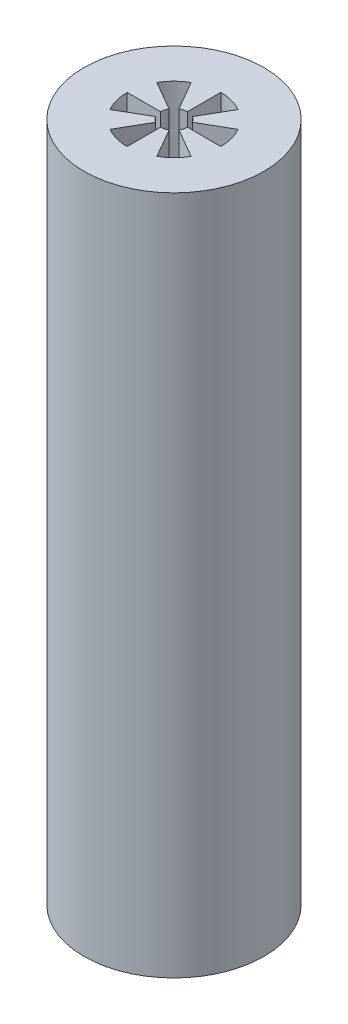
SolidWorks part; units mm, degrees
material "PE High Density"
ref_plane "Front Plane" through (0, 0, 0) normal (0, 0, 1) x (1, 0, 0)
ref_plane "Top Plane" through (0, 0, 0) normal (0, 1, 0) x (1, 0, 0)
ref_plane "Right Plane" through (0, 0, 0) normal (1, 0, 0) x (0, 0, -1)
sketch "Sketch1" plane through (0, 0, 0) normal (0, 1, 0) x (1, 0, 0)
  line L0 (0, 6.35) -> (0, 22.225)
  line L1 (3.175, 5.4993) -> (11.1125, 19.2474)
  line L2 (5.4993, 3.175) -> (19.2474, 11.1125)
  line L3 (6.35, 0) -> (22.225, 0)
  line L4 (5.4993, -3.175) -> (19.2474, -11.1125)
  line L5 (3.175, -5.4993) -> (11.1125, -19.2474)
  line L6 (0, -6.35) -> (0, -22.225)
  line L7 (-3.175, -5.4993) -> (-11.1125, -19.2474)
  line L8 (-5.4993, -3.175) -> (-19.2474, -11.1125)
  line L9 (-6.35, 0) -> (-22.225, 0)
  line L10 (-5.4993, 3.175) -> (-19.2474, 11.1125)
  line L11 (-3.175, 5.4993) -> (-11.1125, 19.2474)
  arc A0 (-5.4993, 3.175) -> (-6.35, 0) centre (0, 0) ccw
  arc A1 (22.225, 0) -> (19.2474, 11.1125) centre (0, 0) ccw
  circle A2 centre (0, 0) radius 42.672
  arc A3 (-5.4993, -3.175) -> (-3.175, -5.4993) centre (0, 0) ccw
  arc A4 (0, -6.35) -> (3.175, -5.4993) centre (0, 0) ccw
  arc A5 (5.4993, -3.175) -> (6.35, 0) centre (0, 0) ccw
  arc A6 (5.4993, 3.175) -> (3.175, 5.4993) centre (0, 0) ccw
  arc A7 (0, 6.35) -> (-3.175, 5.4993) centre (0, 0) ccw
  arc A8 (11.1125, -19.2474) -> (19.2474, -11.1125) centre (0, 0) ccw
  arc A9 (-11.1125, -19.2474) -> (0, -22.225) centre (0, 0) ccw
  arc A10 (-22.225, 0) -> (-19.2474, -11.1125) centre (0, 0) ccw
  arc A11 (-11.1125, 19.2474) -> (-19.2474, 11.1125) centre (0, 0) ccw
  arc A12 (11.1125, 19.2474) -> (0, 22.225) centre (0, 0) ccw
  point P19 (0, 0)
  point P23 (0, 0)
  dimension "D1" = 12
extrude "Boss-Extrude1" add sketch "Sketch1" along normal blind 322.58
